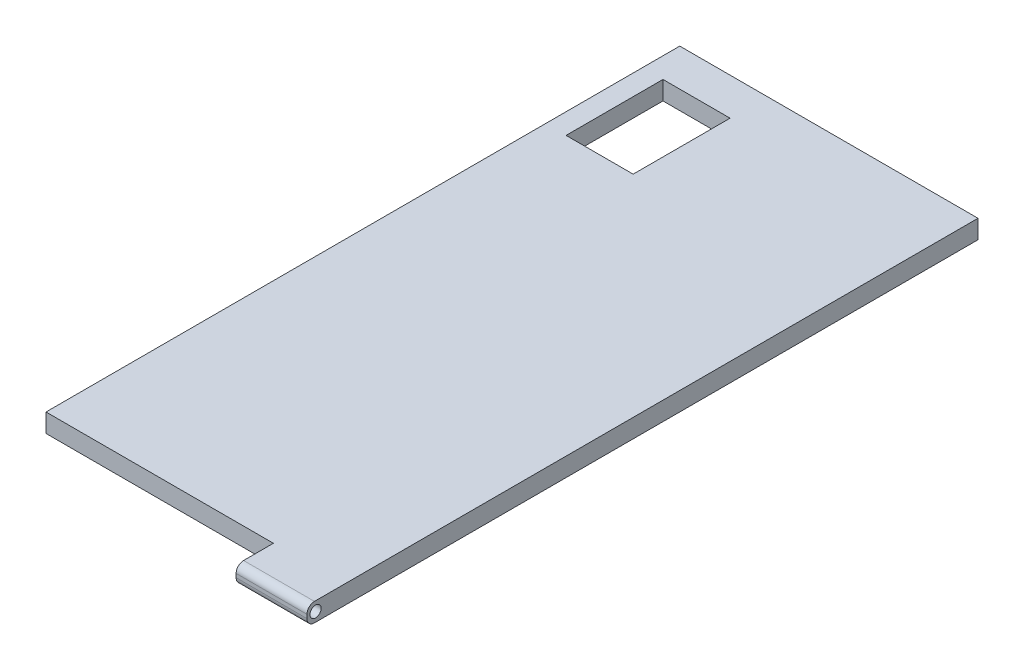
SolidWorks part; units mm, degrees
ref_plane "Front Plane" through (0, 0, 0) normal (0, 0, 1) x (1, 0, 0)
ref_plane "Top Plane" through (0, 0, 0) normal (0, 1, 0) x (1, 0, 0)
ref_plane "Right Plane" through (0, 0, 0) normal (1, 0, 0) x (0, 0, -1)
sketch "Sketch4" plane through (0, 0, 0) normal (0, 1, 0) x (1, 0, 0)
  line L1 (-20, -42.5) -> (20, -42.5)
  line L2 (-20, -42.5) -> (-20, 42.5)
  line L3 (-20, 42.5) -> (20, 42.5)
  line L4 (20, -42.5) -> (20, 42.5)
  line L5 (-20, -42.5) -> (20, 42.5) construction
  line L6 (-20, 42.5) -> (20, -42.5) construction
  point P0 (0, 0)
  dimension "D1" = 85
  dimension "D2" = 40
extrude "Boss-Extrude1" add sketch "Sketch4" along normal blind 2.5
sketch "Sketch5" plane through (0, 2.5, 0) normal (0, 1, 0) x (1, 0, 0)
  line L1 (20, -42.5) -> (10.5, -42.5)
  line L2 (20, -42.5) -> (20, -47.5)
  line L3 (20, -47.5) -> (10.5, -47.5)
  line L4 (10.5, -42.5) -> (10.5, -47.5)
  dimension "D1" = 5
  dimension "D2" = 9.5
extrude "Boss-Extrude2" add sketch "Sketch5" against normal blind 2.5
sketch "Sketch12" plane through (0, 2.5, 0) normal (0, 1, 0) x (1, 0, 0)
  line L1 (-17.25, 37.5) -> (-8.25, 37.5)
  line L2 (-17.25, 37.5) -> (-17.25, 24.5)
  line L3 (-17.25, 24.5) -> (-8.25, 24.5)
  line L4 (-8.25, 37.5) -> (-8.25, 24.5)
  line L7 (20, 42.5) -> (-20, 42.5) construction
  line L8 (-20, 42.5) -> (-20, -42.5) construction
  dimension "D1" = 13
  dimension "D2" = 9
  dimension "D3" = 2.75
  dimension "D4" = 5
extrude "Cut-Extrude1" cut sketch "Sketch12" against normal blind 5
fillet "Fillet4" radius 1 1 edges at (15.25, 2.5, 47.5)
fillet "Fillet5" radius 1 1 edges at (15.25, 0, 47.5)
sketch "Sketch13" plane through (10.5, 0, 0) normal (-1, 0, 0) x (0, 0, 1)
  line L0 (47.5, 1.25) -> (45.2, 1.25) construction
  line L1 (47.5, 1) -> (47.5, 1.5) construction
  circle A0 centre (46.35, 1.25) radius 0.75
  dimension "D1" = 1.5
  dimension "D2" = 1.15
extrude "Cut-Extrude2" cut sketch "Sketch13" against normal blind 10
